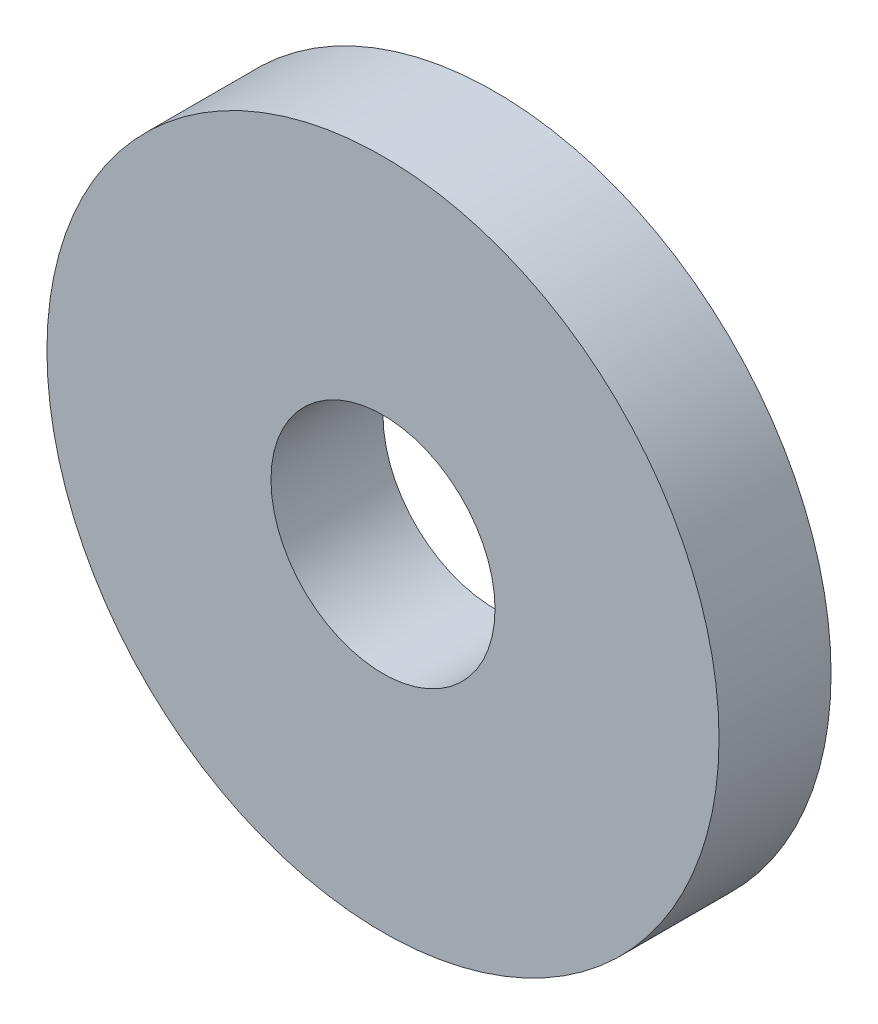
SolidWorks part; units mm, degrees
ref_plane "Спереди" through (0, 0, 0) normal (0, 0, 1) x (1, 0, 0)
ref_plane "Сверху" through (0, 0, 0) normal (0, 1, 0) x (1, 0, 0)
ref_plane "Справа" through (0, 0, 0) normal (1, 0, 0) x (0, 0, -1)
sketch "Эскиз1" plane through (0, 0, 0) normal (0, 0, 1) x (1, 0, 0)
  circle A0 centre (0, 0) radius 3
  circle A1 centre (0, 0) radius 9
extrude "Вытянуть2" add sketch "Эскиз1" along normal blind 3
